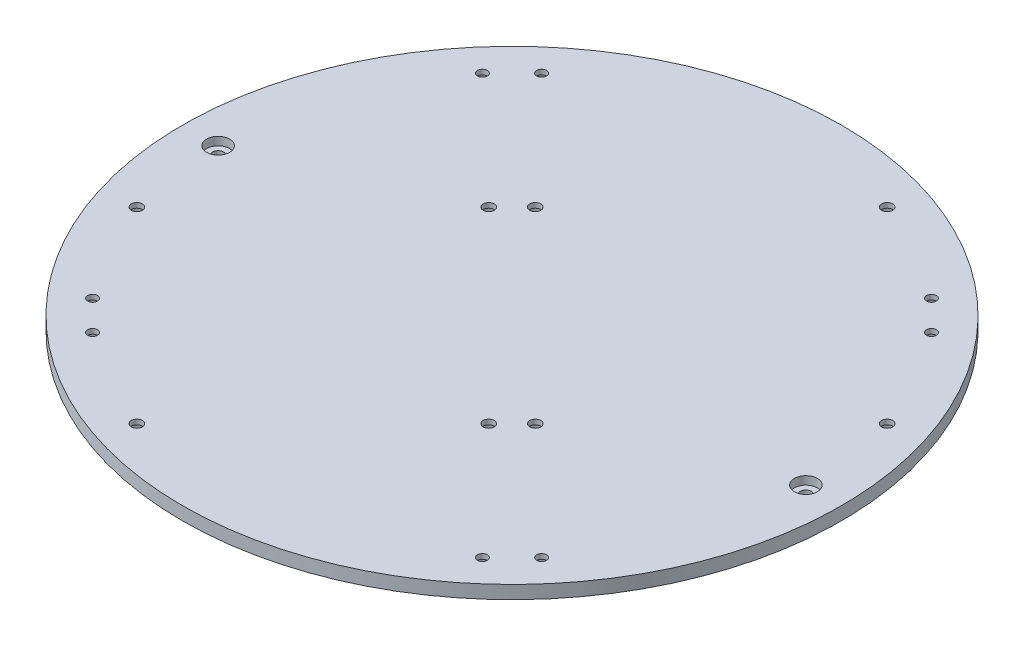
SolidWorks part; units mm, degrees
ref_plane "Front Plane" through (0, 0, 0) normal (0, 0, 1) x (1, 0, 0)
ref_plane "Top Plane" through (0, 0, 0) normal (0, 1, 0) x (1, 0, 0)
ref_plane "Right Plane" through (0, 0, 0) normal (1, 0, 0) x (0, 0, -1)
sketch "Sketch2" plane through (0, 0, 0) normal (0, 1, 0) x (1, 0, 0)
  line L0 (-65, 40) -> (-40, 65) construction
  line L1 (-65, -65) -> (65, -65) construction
  line L2 (-65, -65) -> (-65, 65) construction
  line L3 (-65, 65) -> (65, 65) construction
  line L4 (65, -65) -> (65, 65) construction
  line L5 (-65, -65) -> (65, 65) construction
  line L6 (-65, 65) -> (65, -65) construction
  line L7 (-40, 65) -> (40, 65) construction
  line L8 (40, 65) -> (65, 40) construction
  line L9 (65, 40) -> (65, -40) construction
  line L10 (65, -40) -> (40, -65) construction
  line L11 (40, -65) -> (-40, -65) construction
  line L12 (-40, -65) -> (-65, -40) construction
  line L13 (-65, -40) -> (-65, 40) construction
  line L14 (62.2792, -65) -> (65, -62.2792) construction
  line L15 (-52.5, -52.5) -> (-70.2229, -70.2229) construction
  line L17 (-65, -40) -> (-40, -65) construction
  line L20 (63.6396, -63.6396) -> (70.7107, -70.7107) construction
  line L27 (-65, 0) -> (65, 0) construction
  line L28 (89.175, 0) -> (-89.175, 0)
  circle A0 centre (59.1495, -68.1297) radius 1.49
  circle A2 centre (68.1297, -59.1495) radius 1.49
  circle A3 centre (-59.1495, 68.1297) radius 1.49
  circle A4 centre (-68.1297, 59.1495) radius 1.49
  circle A5 centre (-59.1495, -68.1297) radius 1.49
  circle A6 centre (-68.1297, -59.1495) radius 1.49
  circle A7 centre (68.1297, 59.1495) radius 1.49
  circle A8 centre (59.1495, 68.1297) radius 1.49
  circle A9 centre (0, 0) radius 100
  circle A11 centre (-89.175, 0) radius 1.7
  circle A12 centre (89.175, 0) radius 1.7
  point P0 (0, 0)
  point P41 (0, 0)
  dimension "D14" = 200
  dimension "D15" = 178.35
  dimension "D12" = 2.98
  dimension "D16" = 3.4
  dimension "D1" = 130
  dimension "D2" = 130
  dimension "D3" = 80
  dimension "D4" = 80
  dimension "D5" = 25
  dimension "D6" = 25
  dimension "D7" = 45
  dimension "D8" = 45
  dimension "D9" = 45
  dimension "D10" = 45
  dimension "D11" = 10
  dimension "D13" = 6.35
extrude "Boss-Extrude1" add sketch "Sketch2" along normal blind 4
sketch "Sketch3" plane through (0, 4, 0) normal (0, 1, 0) x (1, 0, 0)
  line L0 (-85.3804, -28.4638) -> (-31.9938, 24.9228)
  line L1 (-24.9228, 31.9938) -> (28.4638, 85.3804)
  line L2 (85.3804, 28.4638) -> (31.9938, -24.9228)
  line L3 (-28.4638, -85.3804) -> (24.9228, -31.9938)
  line L4 (28.4583, -28.4583) -> (-28.4583, 28.4583)
  line L5 (0, 0) -> (0, 100) construction
  line L6 (-85.3804, -28.4638) -> (28.4638, 85.3804) construction
  line L7 (-28.4638, -85.3804) -> (85.3804, 28.4638) construction
  line L8 (-28.4638, -85.3804) -> (-31.6264, -94.8671) construction
  line L9 (24.9228, -31.9938) -> (31.9938, -24.9228) construction
  line L10 (-28.4638, -85.3804) -> (0, 0) construction
  circle A0 centre (-28.4638, -85.3804) radius 1.7
  circle A1 centre (24.9228, -31.9938) radius 1.7
  circle A2 centre (31.9938, -24.9228) radius 1.7
  circle A3 centre (85.3804, 28.4638) radius 1.7
  circle A4 centre (28.4638, 85.3804) radius 1.7
  circle A5 centre (-24.9228, 31.9938) radius 1.7
  circle A6 centre (-31.9938, 24.9228) radius 1.7
  circle A7 centre (-85.3804, -28.4638) radius 1.7
  circle A8 centre (0, 0) radius 100 construction
  point P20 (0, 0)
  point P26 (-28.4583, 28.4583)
  point P27 (28.4583, -28.4583)
  point P28 (-24.8829, -87.9618)
  point P29 (-28.361, -85.2981)
  dimension "D2" = 45
  dimension "D3" = 3.4
  dimension "D1" = 75.5
  dimension "D4" = 10
extrude "Cut-Extrude1" cut sketch "Sketch3" against normal blind 10
sketch "Sketch4" plane through (0, 4, 0) normal (0, 1, 0) x (1, 0, 0)
  circle A0 centre (-89.175, 0) radius 3.5 construction
  circle A1 centre (-85.3804, -28.4638) radius 3.5
  circle A2 centre (-68.1297, -59.1495) radius 3.5
  circle A3 centre (-59.1495, -68.1297) radius 3.5
  circle A4 centre (-28.4638, -85.3804) radius 3.5
  circle A5 centre (59.1495, -68.1297) radius 3.5
  circle A6 centre (68.1297, -59.1495) radius 3.5
  circle A7 centre (89.175, 0) radius 3.5 construction
  circle A8 centre (85.3804, 28.4638) radius 3.5
  circle A9 centre (68.1297, 59.1495) radius 3.5
  circle A10 centre (59.1495, 68.1297) radius 3.5
  circle A11 centre (28.4638, 85.3804) radius 3.5
  circle A12 centre (-59.1495, 68.1297) radius 3.5
  circle A13 centre (-68.1297, 59.1495) radius 3.5
  circle A14 centre (-24.9228, 31.9938) radius 3.5
  circle A15 centre (-31.9938, 24.9228) radius 3.5
  circle A16 centre (31.9938, -24.9228) radius 3.5
  circle A17 centre (24.9228, -31.9938) radius 3.5
  dimension "D1" = 7
extrude "Cut-Extrude2" cut sketch "Sketch4" along normal blind 2.5 from surface at -4 starting at face at (-28.4638, 0, 87.0804)
sketch "Sketch5" plane through (0, 4, 0) normal (0, 1, 0) x (1, 0, 0)
  circle A2 centre (-89.175, 0) radius 3.5
  circle A3 centre (89.175, 0) radius 3.5
  dimension "D1" = 7
extrude "Cut-Extrude3" cut sketch "Sketch5" against normal blind 2.5
